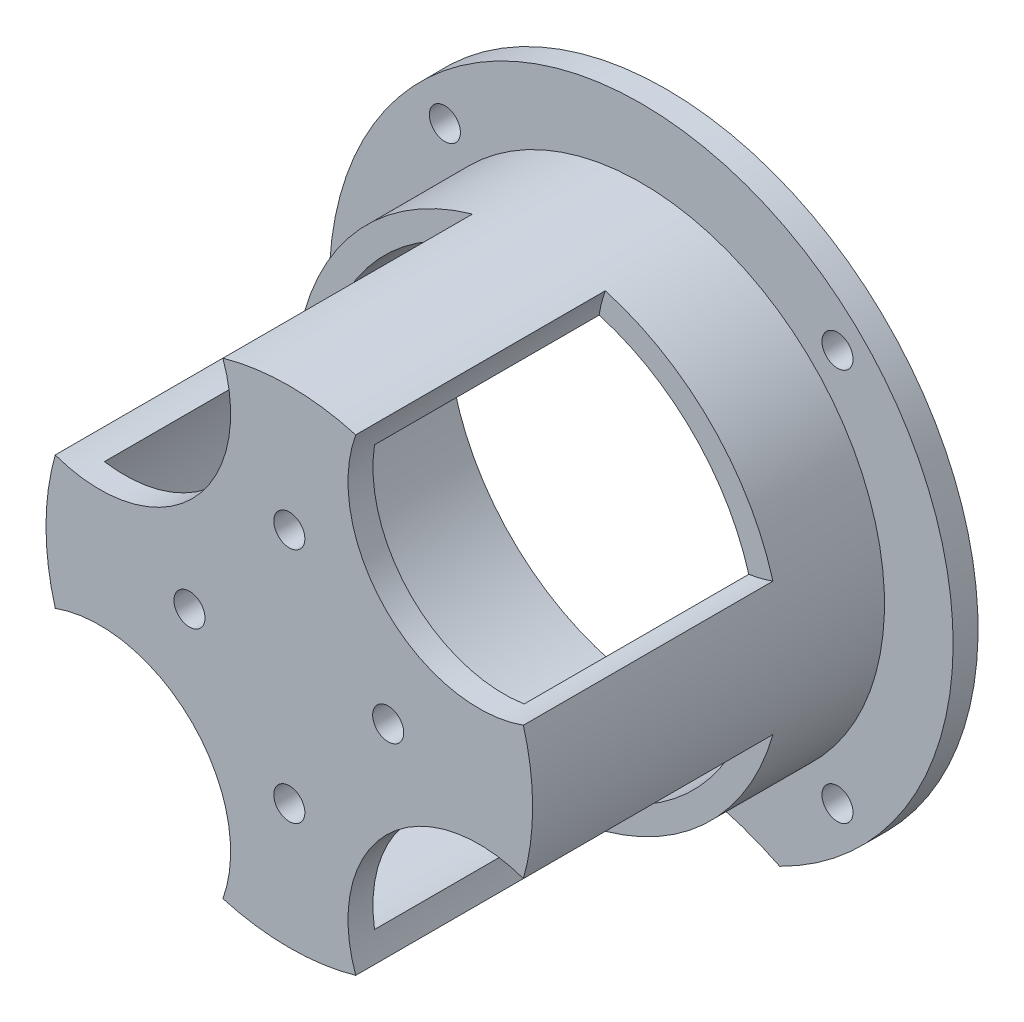
SolidWorks part; units mm, degrees
ref_plane "Спереди" through (0, 0, 0) normal (0, 0, 1) x (1, 0, 0)
ref_plane "Сверху" through (0, 0, 0) normal (0, 1, 0) x (1, 0, 0)
ref_plane "Справа" through (0, 0, 0) normal (1, 0, 0) x (0, 0, -1)
sketch "Эскиз1" plane through (0, 0, 0) normal (0, 1, 0) x (1, 0, 0)
  line L0 (0, 0) -> (0, 14.1) construction
  line L1 (8.75, 1) -> (0, 1)
  line L2 (0, 1) -> (0, 0)
  line L3 (9.75, 15.1) -> (9.75, 0)
  line L5 (8.75, 1) -> (8.75, 15.1)
  line L6 (8.75, 15.1) -> (9.75, 15.1)
  line L7 (0, 0) -> (9.75, 0)
  dimension "D1" = 1
  dimension "D2" = 15.1
  dimension "D3" = 17.5
  dimension "D4" = 1
revolve "Повернуть1" add sketch "Эскиз1" angle 360 about L0
sketch "Эскиз3" plane through (0, 0, 0) normal (0, 0, 1) x (1, 0, 0)
  line L0 (0, 0) -> (7.6014, -7.6014) construction
  line L1 (0, 0) -> (10.75, 0) construction
  circle A0 centre (0, 0) radius 4 construction
  circle A1 centre (0, 0) radius 4.75 construction
  circle A2 centre (-4, 0) radius 0.6225
  circle A3 centre (0, -4.75) radius 0.6225
  circle A4 centre (3.9616, 0) radius 0.6225
  circle A5 centre (0, 4.75) radius 0.6225
  circle A6 centre (0, 0) radius 10.75 construction
  circle A7 centre (7.6014, -7.6014) radius 5.25
  circle A8 centre (-7.6014, -7.6014) radius 5.25
  circle A9 centre (-7.6014, 7.6014) radius 5.25
  circle A10 centre (7.6014, 7.6014) radius 5.25
  point P25 (0, 0)
  dimension "D1" = 9.5
  dimension "D2" = 8
  dimension "D3" = 1.245
  dimension "D4" = 1.245
  dimension "D5" = 1.245
  dimension "D6" = 1.245
  dimension "D7" = 21.5
  dimension "D8" = 10.5
  dimension "D9" = 45
  dimension "D10" = 4
extrude "Вырез-Вытянуть1" cut sketch "Эскиз3" against normal blind 10
sketch "Эскиз4" plane through (0, 0, -15.1) normal (0, 0, -1) x (-1, 0, 0)
  circle A0 centre (0, 0) radius 12.5
  circle A1 centre (0, 0) radius 8.75 construction
  circle A2 centre (0, 0) radius 8.75
  dimension "D1" = 25
extrude "Бобышка-Вытянуть1" add sketch "Эскиз4" against normal blind 1
sketch "Эскиз9" plane through (0, 0, -14.1) normal (0, 0, 1) x (1, 0, 0)
  line L0 (0, 0) -> (7.4264, 7.4264) construction
  circle A0 centre (0, 0) radius 11.125 construction
  circle A1 centre (7.8666, 7.8666) radius 0.6225
  circle A2 centre (7.8666, -7.8666) radius 0.6225
  circle A3 centre (-7.8666, -7.8666) radius 0.6225
  circle A4 centre (-7.8666, 7.8666) radius 0.6225
  point P15 (0, 0)
  dimension "D1" = 22.25
  dimension "D2" = 1.245
  dimension "D3" = 4
extrude "Вырез-Вытянуть2" cut sketch "Эскиз9" against normal through all
sketch "Эскиз10" plane through (0, 0, -14.1) normal (0, 0, 1) x (1, 0, 0)
  line L0 (0, 0) -> (0, -22.4) construction
  circle A0 centre (0, -22.4) radius 12.5
  dimension "D2" = 25
  dimension "D1" = 22.4
extrude "вырез крепления центральной оси" cut sketch "Эскиз10" against normal through all
chamfer "фаска выреза центральной оси" distance 0.5 angle 45 1 edges at (0, -9.9, -15.1)
